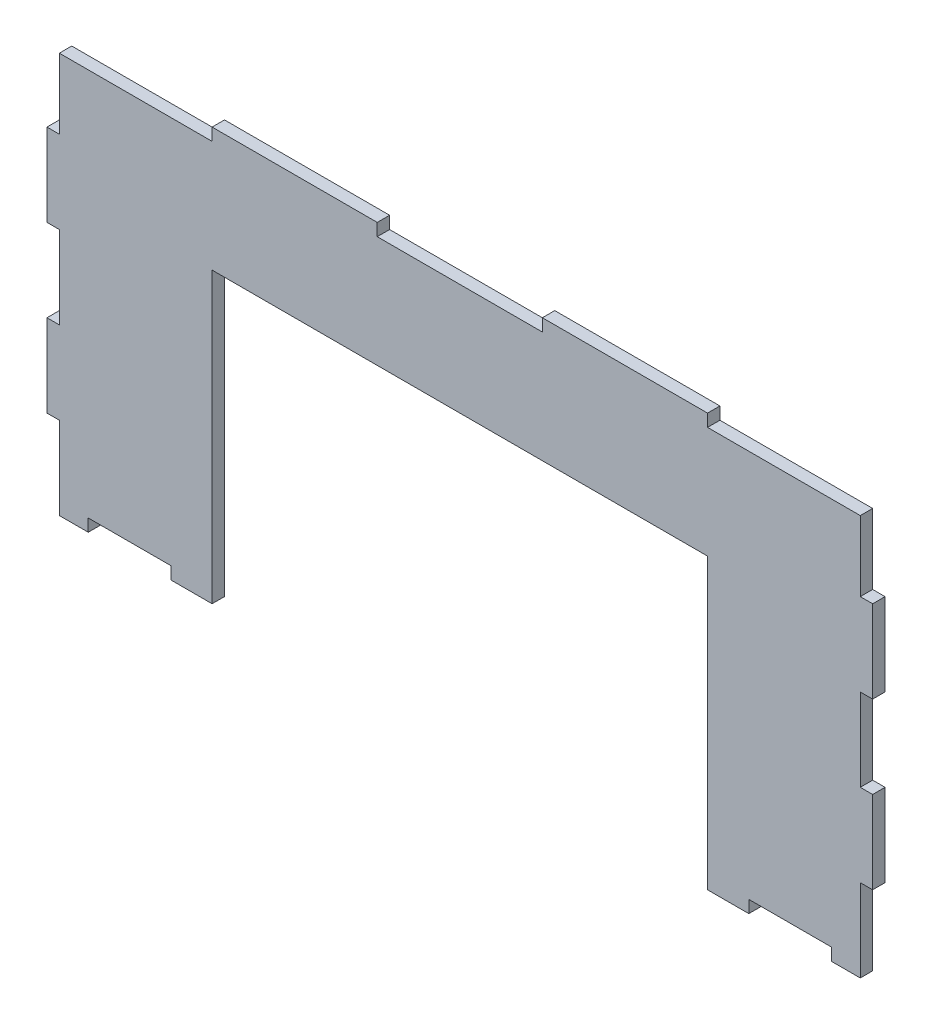
SolidWorks part; units mm, degrees
ref_plane "Alzado" through (0, 0, 0) normal (0, 0, 1) x (1, 0, 0)
ref_plane "Planta" through (0, 0, 0) normal (0, 1, 0) x (1, 0, 0)
ref_plane "Vista lateral" through (0, 0, 0) normal (1, 0, 0) x (0, 0, -1)
sketch "Sketch1" plane through (0, 0, 0) normal (0, 0, 1) x (1, 0, 0)
  line L0 (-60, 5.0977) -> (-60, -50)
  line L1 (-100, 50) -> (100, 50)
  line L2 (-100, 50) -> (-100, -50)
  line L3 (-100, -50) -> (-90, -50)
  line L4 (100, 50) -> (100, -50)
  line L5 (-100, 50) -> (-40, 20) construction
  line L6 (-100, -50) -> (-60, -30) construction
  line L7 (-60, 20) -> (60, 20)
  line L8 (-60, 20) -> (-60, 5.0977)
  line L10 (60, 20) -> (60, -40.1784)
  line L12 (-90, -50) -> (-90, -47)
  line L13 (60, -40.1784) -> (60, -50)
  line L14 (60, -50) -> (70, -50)
  line L15 (-90, -47) -> (-70, -47)
  line L16 (40, 20) -> (100, 50) construction
  line L17 (60, -30) -> (100, -50) construction
  line L18 (-70, -47) -> (-70, -50)
  line L19 (-70, -50) -> (-60, -50)
  line L20 (0, 0) -> (0, -20.1087) construction
  line L21 (70, -47) -> (70, -50)
  line L22 (90, -47) -> (70, -47)
  line L23 (90, -50) -> (90, -47)
  line L25 (90, -50) -> (100, -50)
  point P0 (0, 0)
  point P6 (0, 0)
  dimension "D1" = 200
  dimension "D2" = 100
  dimension "D3" = 120
  dimension "D4" = 40
  dimension "D5" = 10
  dimension "D6" = 30
  dimension "D7" = 20
  dimension "D8" = 3
extrude "Boss-Extrude1" add sketch "Sketch1" along normal blind 3
sketch "Sketch2" plane through (0, 0, 3) normal (0, 0, 1) x (1, 0, 0)
  line L0 (-100, 50) -> (-100, 30) construction
  line L1 (-100, 50) -> (-100, -50) construction
  line L2 (-100, 30) -> (-97, 30)
  line L4 (-97, 10) -> (-100, 10)
  line L5 (100, 50) -> (-100, 50) construction
  line L6 (-100, 10) -> (-100, -10)
  line L7 (-100, -10) -> (-97, -10)
  line L9 (-97, -30) -> (-100, -30)
  line L10 (0, 0) -> (0, -30) construction
  line L17 (-100, 50) -> (-60, 50)
  line L18 (-60, 50) -> (-20, 50)
  line L19 (-100, 50) -> (-100, 47)
  line L20 (20, 50) -> (60, 50)
  line L21 (-60, 50) -> (-60, 47)
  line L22 (-60, 47) -> (-97, 47)
  line L23 (-20, 50) -> (-20, 47)
  line L24 (-20, 47) -> (20, 47)
  line L25 (20, 47) -> (20, 50)
  line L26 (60, 50) -> (60, 47)
  line L27 (60, 47) -> (97, 47)
  line L28 (100, -50) -> (100, 50) construction
  line L29 (-20, 50) -> (20, 50)
  line L30 (60, 50) -> (100, 50)
  line L31 (100, 50) -> (100, 47)
  line L32 (-100, 10) -> (-100, 30)
  line L33 (-100, -10) -> (-100, -30)
  line L34 (100, -30) -> (100, -10)
  line L35 (100, 10) -> (100, 30)
  line L36 (-20, 50) -> (20, 50)
  line L37 (-97, 30) -> (-97, 47)
  line L38 (-97, 10) -> (-97, -10)
  line L39 (-97, -30) -> (-97, -50)
  line L40 (-100, -50) -> (-90, -50) construction
  line L41 (-97, -50) -> (-100, -50)
  line L42 (-100, -50) -> (-100, -30)
  line L43 (-100, -10) -> (-100, 30)
  line L44 (-100, -10) -> (-100, 10)
  line L45 (-100, 30) -> (-100, 50)
  line L46 (-100, 10) -> (-100, -10)
  line L47 (100, 30) -> (100, 50)
  line L48 (100, 30) -> (97, 30)
  line L49 (97, 30) -> (97, 47)
  line L50 (97, 10) -> (100, 10)
  line L51 (100, 10) -> (100, -10)
  line L52 (100, -10) -> (97, -10)
  line L53 (97, 10) -> (97, -10)
  line L54 (100, -50) -> (100, -30)
  line L55 (97, -50) -> (100, -50)
  line L56 (97, -30) -> (97, -50)
  line L57 (97, -30) -> (100, -30)
  line L58 (100, 10) -> (100, -10)
  line M15 (90, -50) -> (100, -50)
  line M16 (100, -50) -> (100, 50)
  line M17 (100, 50) -> (-100, 50)
  line M18 (-100, 50) -> (-100, -50)
  line M19 (-100, -50) -> (-90, -50)
  dimension "D1" = 20
  dimension "D2" = 20
  dimension "D3" = 20
  dimension "D4" = 3
  dimension "D5" = 20
  dimension "D6" = 40
  dimension "D7" = 40
  dimension "D8" = 40
  dimension "D9" = 40
  dimension "D11" = 3
  dimension "D12" = 3
extrude "Cut-Extrude2" cut sketch "Sketch2" against normal blind 3 contours L2 L37 L22 L21 M17 M18 | L38 L4 L7 M18 | L39 L9 M18 M19 | L24 L25 L23 M17 | L49 L48 L26 L27 M16 M17 | L50 L53 L52 M16 | L57 L56 M15 M16
